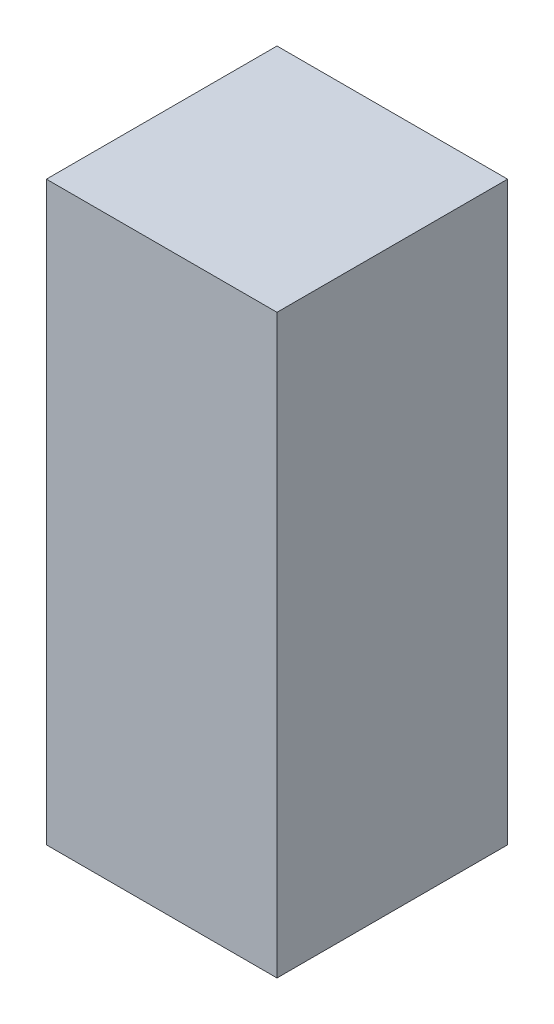
SolidWorks part; units mm, degrees
ref_plane "Front" through (0, 0, 0) normal (0, 0, 1) x (1, 0, 0)
ref_plane "Top" through (0, 0, 0) normal (0, 1, 0) x (1, 0, 0)
ref_plane "Right" through (0, 0, 0) normal (1, 0, 0) x (0, 0, -1)
sketch "Эскиз1" plane through (0, 0, 0) normal (0, 1, 0) x (1, 0, 0)
  line L1 (-487.2474, -647.0304) -> (-447.2474, -647.0304)
  line L2 (-487.2474, -647.0304) -> (-487.2474, -687.0304)
  line L3 (-487.2474, -687.0304) -> (-447.2474, -687.0304)
  line L4 (-447.2474, -647.0304) -> (-447.2474, -687.0304)
  dimension "D1" = 40
  dimension "D2" = 40
extrude "Бобышка-Вытянуть1" add sketch "Эскиз1" along normal blind 100
